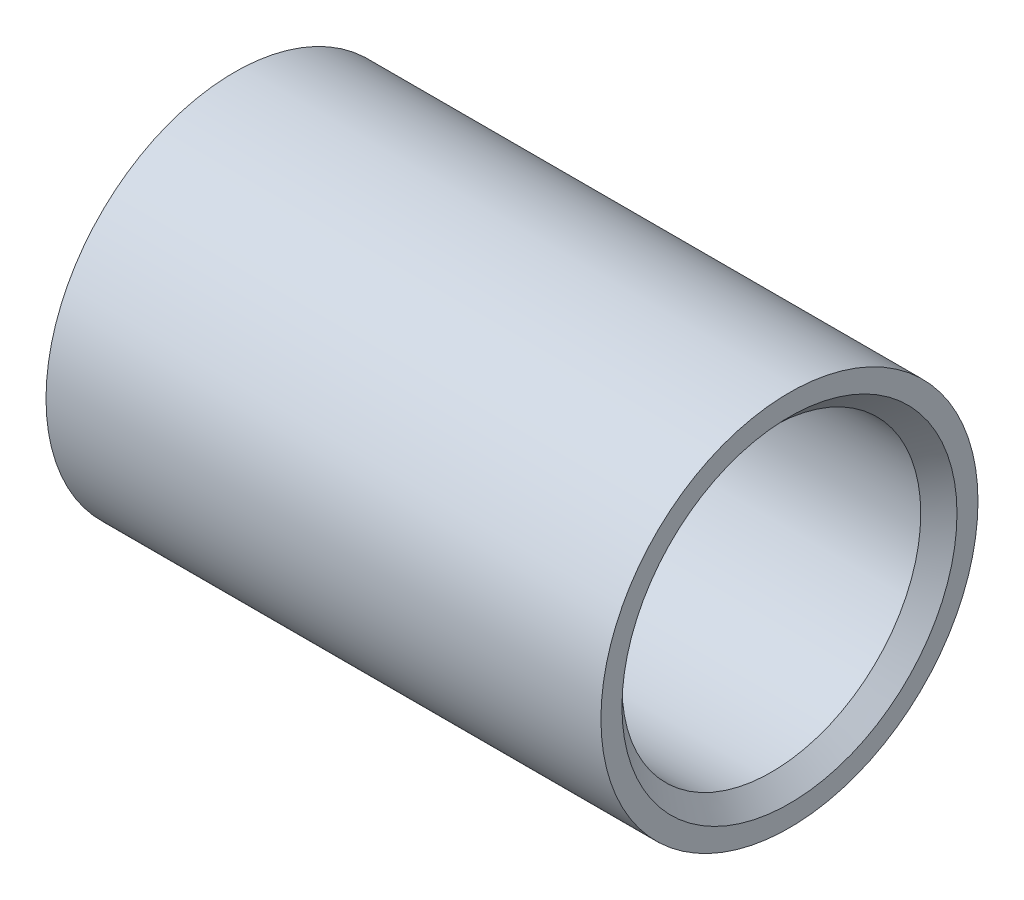
SolidWorks part; units mm, degrees
ref_plane "Front Plane" through (0, 0, 0) normal (0, 0, 1) x (1, 0, 0)
ref_plane "Top Plane" through (0, 0, 0) normal (0, 1, 0) x (1, 0, 0)
ref_plane "Right Plane" through (0, 0, 0) normal (1, 0, 0) x (0, 0, -1)
sketch "Sketch1" plane through (0, 0, 0) normal (0, 0, 1) x (1, 0, 0)
  line L0 (0, 0) -> (39.624, 0) construction
  line L1 (0, 13.462) -> (39.624, 13.462)
  line L2 (39.624, 13.462) -> (39.624, 11.962)
  line L3 (39.624, 11.962) -> (38.33, 10.668)
  line L4 (38.33, 10.668) -> (1.294, 10.668)
  line L5 (1.294, 10.668) -> (0, 11.962)
  line L6 (0, 11.962) -> (0, 13.462)
  dimension "D1" = 135
  dimension "D2" = 26.924
  dimension "D3" = 21.336
  dimension "D4" = 1.5
  dimension "D5" = 39.624
revolve "Revolve1" add sketch "Sketch1" angle 360 about L0
